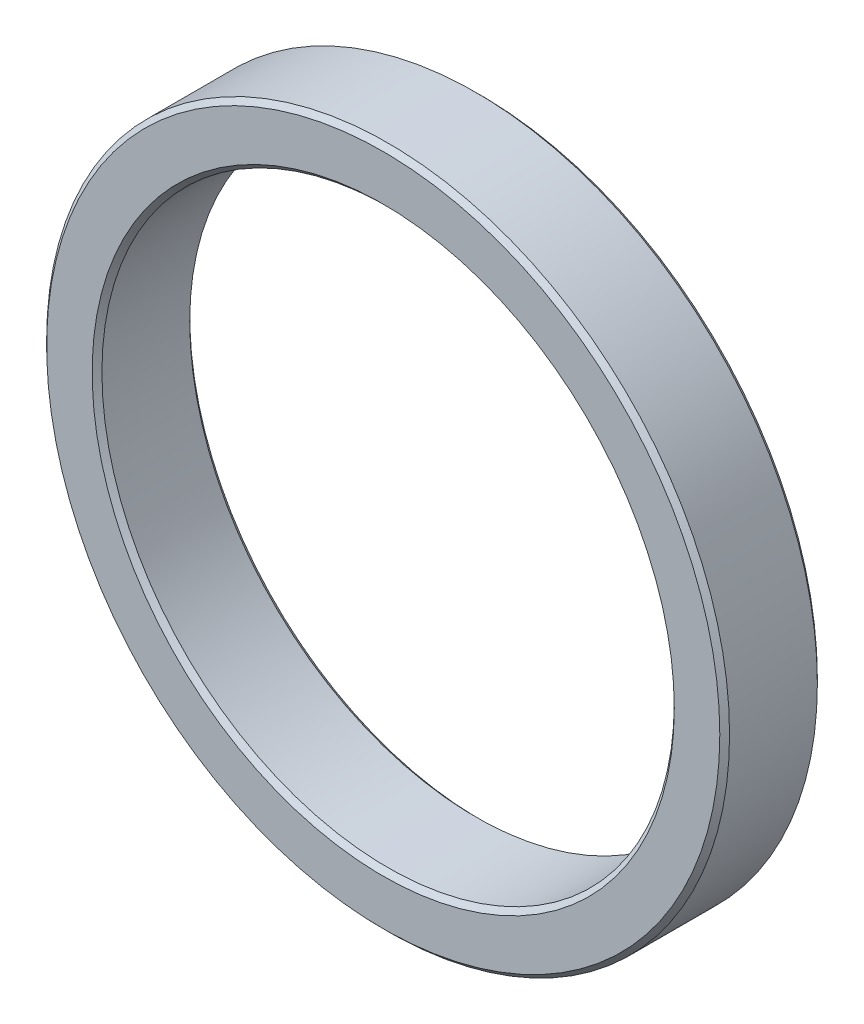
SolidWorks part; units mm, degrees
ref_plane "前视基准面" through (0, 0, 0) normal (0, 0, 1) x (1, 0, 0)
ref_plane "上视基准面" through (0, 0, 0) normal (0, 1, 0) x (1, 0, 0)
ref_plane "右视基准面" through (0, 0, 0) normal (1, 0, 0) x (0, 0, -1)
sketch "草图1" plane through (0, 0, 0) normal (0, 0, 1) x (1, 0, 0)
  circle A0 centre (0, 0) radius 21
  circle A1 centre (0, 0) radius 17.6
extrude "拉伸1" add sketch "草图1" along normal blind 6
chamfer "倒角1" distance 0.3 angle 45 4 edges at (21, 0, 0) (21, 0, 6) (17.6, 0, 0) (17.6, 0, 6)
